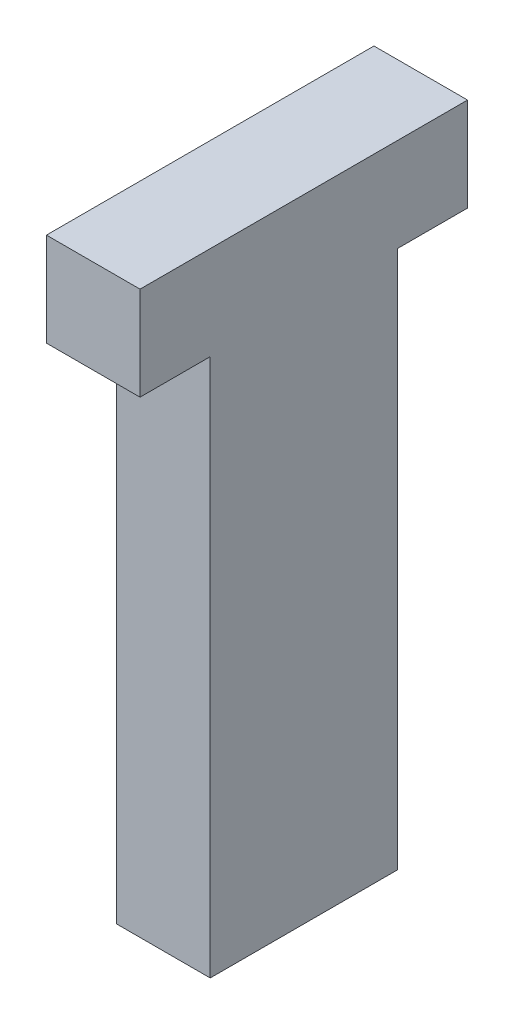
SolidWorks part; units mm, degrees
material "Plain Carbon Steel"
ref_plane "Front Plane" through (0, 0, 0) normal (0, 0, 1) x (1, 0, 0)
ref_plane "Top Plane" through (0, 0, 0) normal (0, 1, 0) x (1, 0, 0)
ref_plane "Right Plane" through (0, 0, 0) normal (1, 0, 0) x (0, 0, -1)
sketch "Sketch1" plane through (0, 0, 0) normal (0, 1, 0) x (1, 0, 0)
  line L1 (0, 0) -> (-10, 0)
  line L2 (0, 0) -> (0, 20)
  line L3 (0, 20) -> (-10, 20)
  line L4 (-10, 0) -> (-10, 20)
  dimension "D1" = 20
  dimension "D2" = 10
extrude "Boss-Extrude1" add sketch "Sketch1" along normal blind 57.5
sketch "Sketch3" plane through (0, 57.5, 0) normal (0, 1, 0) x (1, 0, 0)
  line L6 (-10, 10) -> (-10, 27.5)
  line L7 (-10, 20) -> (-10, 0) construction
  line L8 (-10, 27.5) -> (0, 27.5)
  line L9 (0, 27.5) -> (0, 0)
  line L10 (0, 0) -> (0, -7.5)
  line L11 (0, -7.5) -> (-10, -7.5)
  line L12 (-10, -7.5) -> (-10, 10)
  line L13 (0, 20) -> (-10, 20) construction
  line L14 (-10, 0) -> (0, 0) construction
  dimension "D1" = 7.5
  dimension "D2" = 7.5
extrude "Boss-Extrude2" add sketch "Sketch3" along normal blind 10
